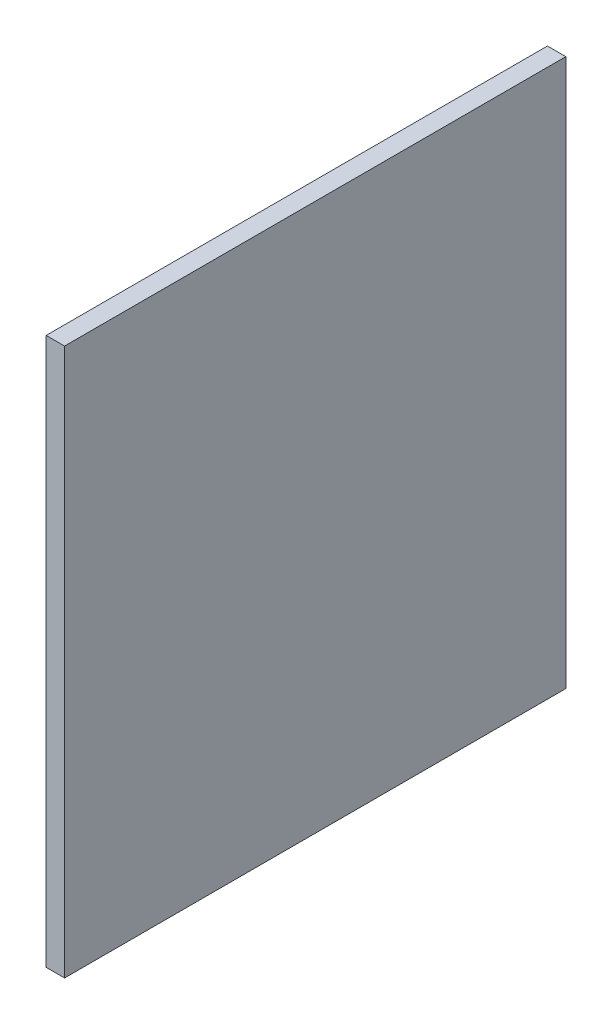
SolidWorks part; units mm, degrees
ref_plane "Front Plane" through (0, 0, 0) normal (0, 0, 1) x (1, 0, 0)
ref_plane "Top Plane" through (0, 0, 0) normal (0, 1, 0) x (1, 0, 0)
ref_plane "Right Plane" through (0, 0, 0) normal (1, 0, 0) x (0, 0, -1)
sketch "Sketch1" plane through (0, 0, 0) normal (1, 0, 0) x (0, 0, -1)
  line L1 (0, 0) -> (490, 0)
  line L2 (0, 0) -> (0, 535)
  line L3 (0, 535) -> (490, 535)
  line L4 (490, 0) -> (490, 535)
  dimension "D1" = 490
  dimension "D2" = 535
extrude "Boss-Extrude1" add sketch "Sketch1" along normal blind 18
